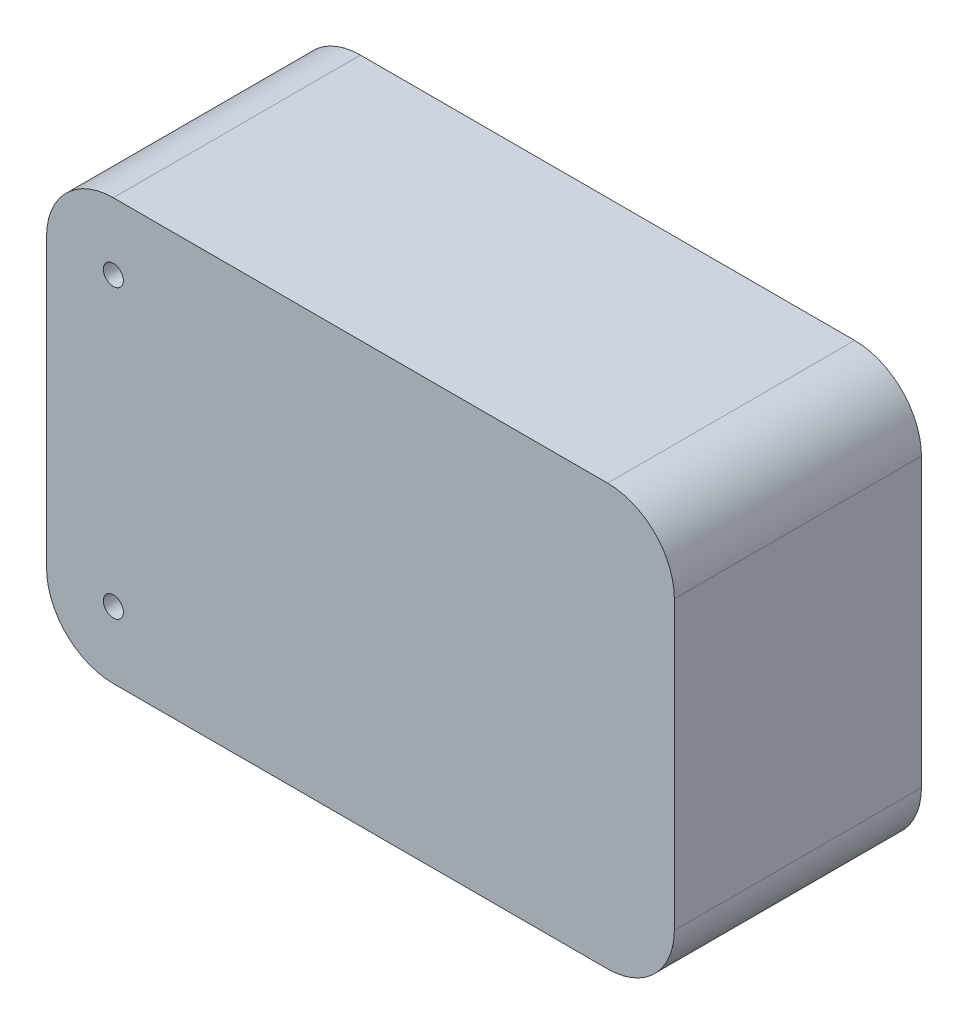
SolidWorks part; units mm, degrees
ref_plane "Front" through (0, 0, 0) normal (0, 0, 1) x (1, 0, 0)
ref_plane "Top" through (0, 0, 0) normal (0, 1, 0) x (1, 0, 0)
ref_plane "Right" through (0, 0, 0) normal (1, 0, 0) x (0, 0, -1)
sketch "草图1" plane through (0, 0, 0) normal (0, 0, 1) x (1, 0, 0)
  line L1 (-49.5556, 31) -> (44.4444, 31)
  line L2 (-49.5556, 31) -> (-49.5556, -32)
  line L3 (-49.5556, -32) -> (44.4444, -32)
  line L4 (44.4444, 31) -> (44.4444, -32)
  dimension "D1" = 94
  dimension "D2" = 63
extrude "凸台-拉伸1" add sketch "草图1" along normal blind 37
fillet "圆角1" radius 10 4 edges at (-49.5556, 31, 18.5) (-49.5556, -32, 18.5) (44.4444, 31, 18.5) (44.4444, -32, 18.5)
sketch "草图3" plane through (0, 0, 37) normal (0, 0, 1) x (1, 0, 0)
  circle A2 centre (-39.5556, -22) radius 1.5
  circle A3 centre (-39.5556, 21) radius 1.5
extrude "切除-拉伸1" cut sketch "草图3" against normal blind 10
